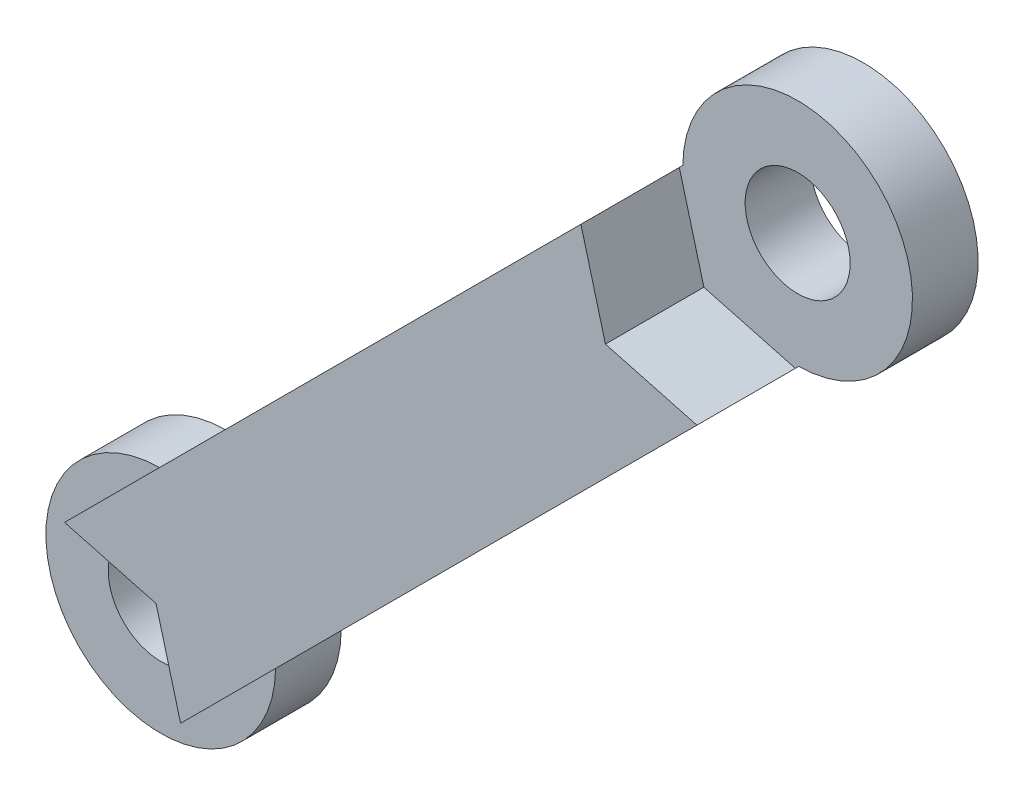
SolidWorks part; units mm, degrees
material "PLA"
ref_plane "Front Plane" through (0, 0, 0) normal (0, 0, 1) x (1, 0, 0)
ref_plane "Top Plane" through (0, 0, 0) normal (0, 1, 0) x (1, 0, 0)
ref_plane "Right Plane" through (0, 0, 0) normal (1, 0, 0) x (0, 0, -1)
sketch "Sketch1" plane through (0, 0, 0) normal (0, 0, 1) x (1, 0, 0)
  line L0 (12.0208, 12.0208) -> (29.6985, 29.6985) construction
  line L1 (27.9307, 31.4663) -> (31.4663, 27.9307)
  line L2 (27.9307, 31.4663) -> (11.9851, 15.5206)
  line L3 (31.4663, 27.9307) -> (15.5206, 11.9851)
  line L4 (12.0208, 12.0208) -> (23.7939, 12.0208) construction
  line L5 (19.9579, 23.4934) -> (23.4934, 19.9579) construction
  circle A0 centre (12.0208, 12.0208) radius 1.6
  circle A1 centre (12.0208, 12.0208) radius 3.5
  circle A2 centre (31.4305, 31.4305) radius 1.6
  circle A3 centre (31.4305, 31.4305) radius 3.5
  point P7 (29.6985, 29.6985)
  dimension "D1" = 7
  dimension "D2" = 25
  dimension "D3" = 5
  dimension "D5" = 3.2
  dimension "D4" = 45
extrude "Boss-Extrude1" add sketch "Sketch1" along normal blind 5
sketch "Sketch2" plane through (0, 0, 5) normal (0, 0, 1) x (1, 0, 0)
  line L0 (12.0208, 12.0208) -> (31.4305, 31.4305) construction
  line L7 (9.1631, 9.1631) -> (13.0668, 8.1171)
  line L8 (13.0668, 8.1171) -> (15.9246, 10.9748)
  line L9 (15.9246, 10.9748) -> (14.8786, 14.8786)
  line L10 (14.8786, 14.8786) -> (10.9748, 15.9246)
  line L11 (10.9748, 15.9246) -> (8.1171, 13.0668)
  line L12 (8.1171, 13.0668) -> (9.1631, 9.1631)
  line L13 (32.4765, 27.5268) -> (35.3343, 30.3845)
  line L14 (15.5206, 11.9851) -> (31.4663, 27.9307)
  line L15 (27.9307, 31.4663) -> (11.9851, 15.5206)
  line L16 (15.5206, 11.9851) -> (31.4663, 27.9307)
  line L17 (27.9307, 31.4663) -> (11.9851, 15.5206)
  line L18 (35.3343, 30.3845) -> (34.2883, 34.2883)
  line L19 (34.2883, 34.2883) -> (30.3845, 35.3343)
  line L20 (30.3845, 35.3343) -> (27.5268, 32.4765)
  line L21 (27.5268, 32.4765) -> (28.5728, 28.5728)
  line L22 (28.5728, 28.5728) -> (32.4765, 27.5268)
  circle A2 centre (31.4305, 31.4305) radius 3.5 construction
  circle A3 centre (12.0208, 12.0208) radius 3.5 construction
  arc A5 (11.9851, 15.5206) -> (15.5206, 11.9851) centre (12.0208, 12.0208) ccw
  arc A6 (31.4663, 27.9307) -> (27.9307, 31.4663) centre (31.4305, 31.4305) ccw
  arc A7 (11.9851, 15.5206) -> (15.5206, 11.9851) centre (12.0208, 12.0208) ccw
  arc A8 (31.4663, 27.9307) -> (27.9307, 31.4663) centre (31.4305, 31.4305) ccw
  point P0 (0, 0)
  dimension "D1" = 0
  dimension "D2" = 7
extrude "Cut-Extrude1" cut sketch "Sketch2" against normal blind 3
